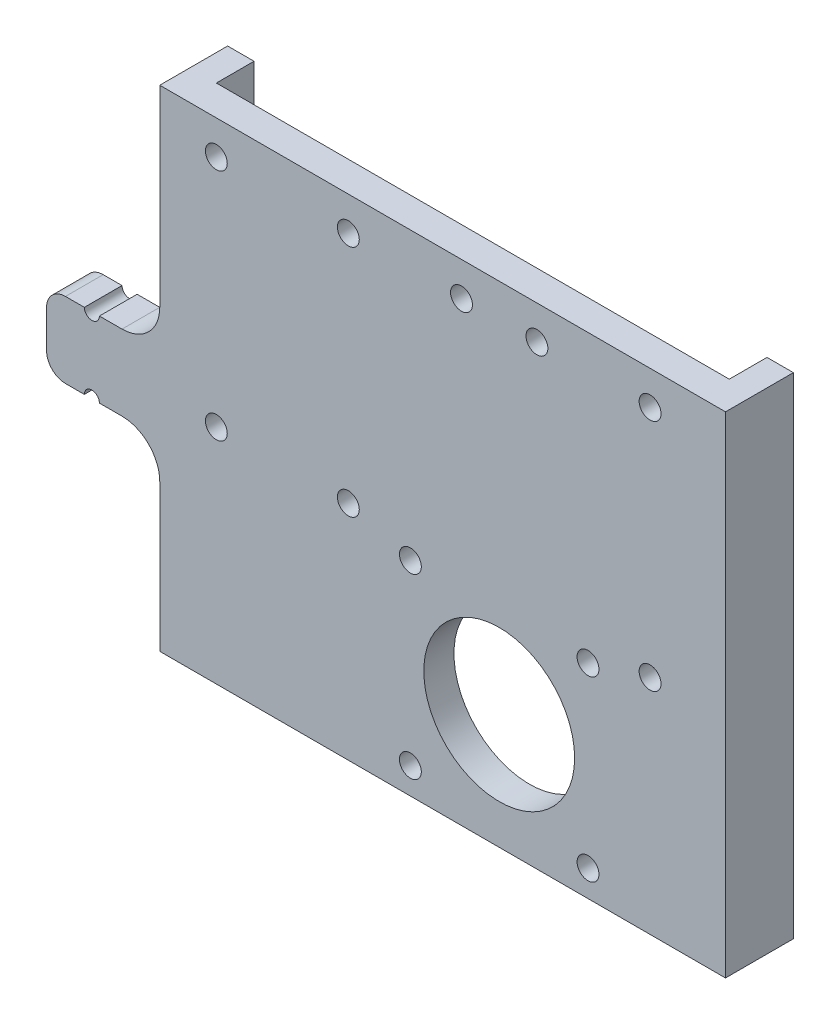
SolidWorks part; units mm, degrees
material "Acrylic (Medium-high impact)"
ref_plane "Front Plane" through (0, 0, 0) normal (0, 0, 1) x (1, 0, 0)
ref_plane "Top Plane" through (0, 0, 0) normal (0, 1, 0) x (1, 0, 0)
ref_plane "Right Plane" through (0, 0, 0) normal (1, 0, 0) x (0, 0, -1)
sketch "Sketch1" plane through (0, 0, 0) normal (0, 0, 1) x (1, 0, 0)
  line L1 (-50, 65) -> (50, 65)
  line L2 (-50, 65) -> (-50, -65)
  line L3 (-50, -65) -> (50, -65)
  line L4 (50, 65) -> (50, -65)
  line L5 (-50, 65) -> (50, -65) construction
  line L6 (-50, -65) -> (50, 65) construction
  point P0 (0, 0)
  dimension "D1" = 100
  dimension "D2" = 130
extrude "Boss-Extrude1" add sketch "Sketch1" along normal blind 8
sketch "Sketch4" plane through (0, 0, 8) normal (0, 0, 1) x (1, 0, 0)
  line L0 (-50, -65) -> (50, -65) construction
  line L1 (50, 65) -> (-50, 65) construction
  line L2 (-50, 65) -> (-50, -65) construction
  line L3 (50, -65) -> (50, 65) construction
  point P0 (-40, 6)
  point P2 (40, 6)
  point P4 (-40, -56)
  point P6 (40, -56)
  point P14 (-23.55, 58)
  point P16 (23.55, 58)
  point P17 (-23.55, 10.9)
  point P19 (23.55, 10.9)
  point P43 (-10, -56)
  point P46 (10, -56)
  dimension "D1" = 62
  dimension "D3" = 9
  dimension "D6" = 47.1
  dimension "D7" = 7
  dimension "D8" = 47.1
  dimension "D9" = 23.55
  dimension "D2" = 10
  dimension "D4" = 10
  dimension "D5" = 20
  dimension "D10" = 10
hole_wizard "M5 Clearance Hole1" positions "Sketch4" profile "Sketch3" hole size "M5" standard "ISO" end condition through all
sketch "Sketch3" plane through (-40, 6, 8) normal (1, 0, 0) x (0, -1, 0)
  line L0 (0, 0) -> (0, 8)
  line L1 (0, 8) -> (2.9, 8)
  line L2 (2.9, 8) -> (2.9, 0)
  line L5 (2.9, 0) -> (0, 0)
  line L11 (0, -6.35) -> (0, 107.95) construction
  dimension "Thru Hole Dia." = 5.8
  dimension "Thru Hole Depth" = 8
sketch "Sketch6" plane through (0, 0, 8) normal (0, 0, 1) x (1, 0, 0)
  circle A0 centre (0, 34.5) radius 20
  circle A1 centre (-23.55, 58) radius 2.9 construction
  dimension "D1" = 40
  dimension "D2" = 23.5
extrude "Cut-Extrude1" cut sketch "Sketch6" against normal blind 10
sketch "Sketch9" plane through (0, 0, 8) normal (0, 0, 1) x (1, 0, 0)
  line L0 (-50, -65) -> (50, -65) construction
  line L1 (-50, 65) -> (-90, 65)
  line L2 (-50, 65) -> (-50, -65)
  line L3 (-50, -65) -> (-90, -65)
  line L4 (-90, 65) -> (-90, -65)
  line L6 (50, 65) -> (60, 65)
  line L7 (50, 65) -> (50, -65)
  line L8 (50, -65) -> (60, -65)
  line L9 (60, 65) -> (60, -65)
  dimension "D1" = 40
  dimension "D2" = 10
extrude "Boss-Extrude2" add sketch "Sketch9" against normal up to surface (8 mm away) up to face at (20, 34.5, 0)
sketch "Sketch12" plane through (0, 0, 8) normal (0, 0, 1) x (1, 0, 0)
  point P0 (-75, 6)
  point P2 (-75, -56)
  dimension "D1" = 35
hole_wizard "M5 Clearance Hole2" positions "Sketch12" profile "Sketch11" hole size "M5" standard "ANSI Metric" end condition through all
sketch "Sketch11" plane through (-75, 6, 8) normal (1, 0, 0) x (0, -1, 0)
  line L0 (0, 0) -> (0, 8)
  line L1 (0, 8) -> (2.9, 8)
  line L2 (2.9, 8) -> (2.9, 0)
  line L5 (2.9, 0) -> (0, 0)
  line L11 (0, -6.35) -> (0, 107.95) construction
  dimension "Thru Hole Dia." = 5.8
  dimension "Thru Hole Depth" = 8
sketch "Sketch8" plane through (0, 0, 8) normal (0, 0, 1) x (1, 0, 0)
  line L0 (-50, -25) -> (50, -25) construction
  circle A1 centre (-40, 6) radius 2.9 construction
  dimension "D1" = 31
ref_plane "Plane1" through (0, -25, 0) normal (0, -1, 0) x (1, 0, 0)
sketch "Sketch13" plane through (0, 0, 0) normal (0, 0, -1) x (-1, 0, 0)
  line L0 (90, -65) -> (-60, -65) construction
  line L1 (-60, 65) -> (-53, 65)
  line L2 (-60, 65) -> (-60, -65)
  line L3 (-60, -65) -> (-53, -65)
  line L4 (-53, 65) -> (-53, -65)
  line L6 (90, 65) -> (83, 65)
  line L7 (90, 65) -> (90, -65)
  line L8 (90, -65) -> (83, -65)
  line L9 (83, 65) -> (83, -65)
  dimension "D1" = 7
  dimension "D2" = 7
extrude "Boss-Extrude3" add sketch "Sketch13" along normal blind 10
sketch "Sketch14" plane through (0, 0, 8) normal (0, 0, 1) x (1, 0, 0)
  line L0 (-90, 65) -> (-90, -65) construction
  line L1 (-90, 16) -> (-120, 16)
  line L2 (-90, 16) -> (-90, -4)
  line L3 (-90, -4) -> (-120, -4)
  line L4 (-120, 16) -> (-120, -4)
  point P6 (-90, 6)
  dimension "D1" = 20
  dimension "D2" = 30
extrude "Boss-Extrude4" add sketch "Sketch14" against normal blind 10
fillet "Fillet1" radius 10 2 edges at (-90, -4, 3) (-90, 16, 3)
fillet "Fillet2" radius 5 2 edges at (-120, 16, 3) (-120, -4, 3)
sketch "Sketch15" plane through (0, 0, -2) normal (0, 0, -1) x (-1, 0, 0)
  line L0 (106, 16) -> (110, 16)
  line L1 (100, 16) -> (115, 16) construction
  line L2 (110, -4) -> (106, -4)
  line L3 (115, -4) -> (100, -4) construction
  line L4 (120, 11) -> (120, 1) construction
  arc A0 (110, 16) -> (106, 16) centre (108, 16) cw
  arc A1 (106, -4) -> (110, -4) centre (108, -4) cw
  dimension "D1" = 2
  dimension "D2" = 12
extrude "Cut-Extrude2" cut sketch "Sketch15" against normal up to next
mirror "Mirror1" about plane through (0, 0, 0) normal (0, 1, 0) of bodies 108
delete or keep bodies "Body-Delete/Keep 1" type delete bodies bodies 108
equation "\"Roller_Wheel_Gap\"=62"
equation "\"D1@Sketch4\"=\"Roller_Wheel_Gap\""
equation "\"D1@Sketch8\"=\"Roller_Wheel_Gap\"/2"
